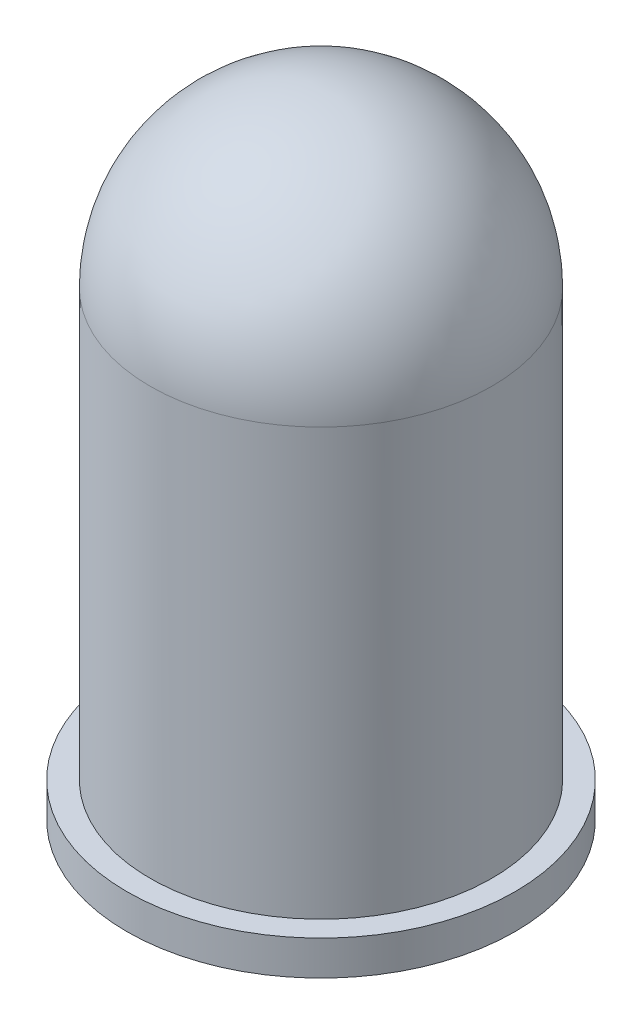
SolidWorks part; units mm, degrees
ref_plane "Front Plane" through (0, 0, 0) normal (0, 0, 1) x (1, 0, 0)
ref_plane "Top Plane" through (0, 0, 0) normal (0, 1, 0) x (1, 0, 0)
ref_plane "Right Plane" through (0, 0, 0) normal (1, 0, 0) x (0, 0, -1)
sketch "Sketch1" plane through (0, 0, 0) normal (0, 0, 1) x (1, 0, 0)
  line L0 (0, 46.4355) -> (0, -43.22) construction
  line L1 (-24.662, 18.2774) -> (-24.662, -43.22)
  line L2 (-24.662, -43.22) -> (0, -43.22)
  line L3 (0, -43.22) -> (0, 42.9394)
  arc A0 (0, 42.9394) -> (-24.662, 18.2774) centre (0, 18.2774) ccw
revolve "Revolve1" add sketch "Sketch1" angle 360 about L3
sketch "Sketch2" plane through (0, -43.22, 0) normal (0, -1, 0) x (1, 0, 0)
  circle A0 centre (0, 0) radius 28
extrude "Boss-Extrude1" add sketch "Sketch2" along normal blind 5
sketch "Sketch3" plane through (0, -48.22, 0) normal (0, -1, 0) x (1, 0, 0)
  line L1 (2.5, -10) -> (-2.5, -10)
  line L2 (2.5, -10) -> (2.5, 10)
  line L3 (2.5, 10) -> (-2.5, 10)
  line L4 (-2.5, -10) -> (-2.5, 10)
  line L5 (2.5, -10) -> (-2.5, 10) construction
  line L6 (2.5, 10) -> (-2.5, -10) construction
  point P0 (0, 0)
  dimension "D1" = 5
  dimension "D2" = 20
extrude "Cut-Extrude1" cut sketch "Sketch3" against normal blind 10
